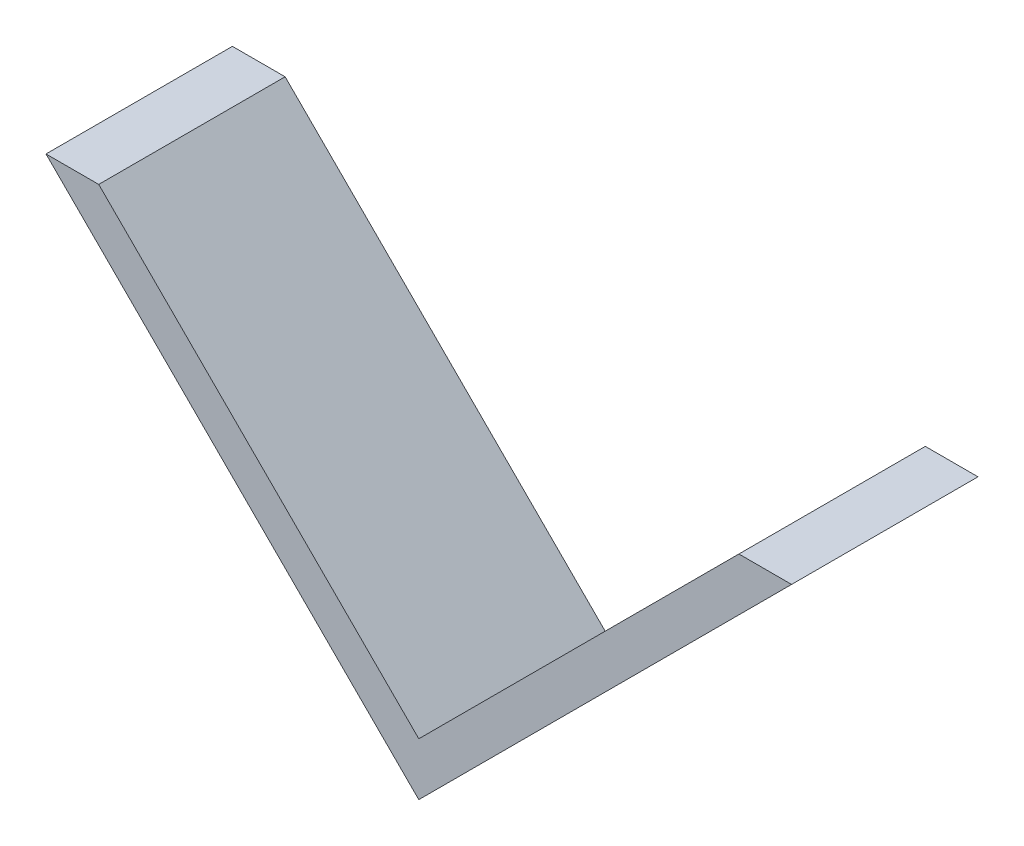
SolidWorks part; units mm, degrees
ref_plane "Front Plane" through (0, 0, 0) normal (0, 0, 1) x (1, 0, 0)
ref_plane "Top Plane" through (0, 0, 0) normal (0, 1, 0) x (1, 0, 0)
ref_plane "Right Plane" through (0, 0, 0) normal (1, 0, 0) x (0, 0, -1)
sketch "Sketch1" plane through (0, 0, 0) normal (0, 0, 1) x (1, 0, 0)
  line L0 (0, 0) -> (20, 20)
  line L1 (20, 20) -> (-20, 20)
  line L2 (-20, 20) -> (0, 0)
  line L3 (0, 0) -> (0, 20) construction
  dimension "D1" = 90
  dimension "D2" = 20
extrude "Boss-Extrude1" add sketch "Sketch1" along normal mid plane 10
sketch "Sketch2" plane through (0, 0, 5) normal (0, 0, 1) x (1, 0, 0)
  line L0 (0, 2.8284) -> (-17.1716, 20)
  line L1 (20, 20) -> (-20, 20) construction
  line L2 (-17.1716, 20) -> (17.1716, 20)
  line L3 (17.1716, 20) -> (0, 2.8284)
  line L4 (0, 0) -> (20, 20) construction
  line L5 (0, 0) -> (0, 20) construction
  line L6 (-20, 20) -> (0, 0) construction
  dimension "D1" = 2
extrude "Cut-Extrude1" cut sketch "Sketch2" against normal blind 10
